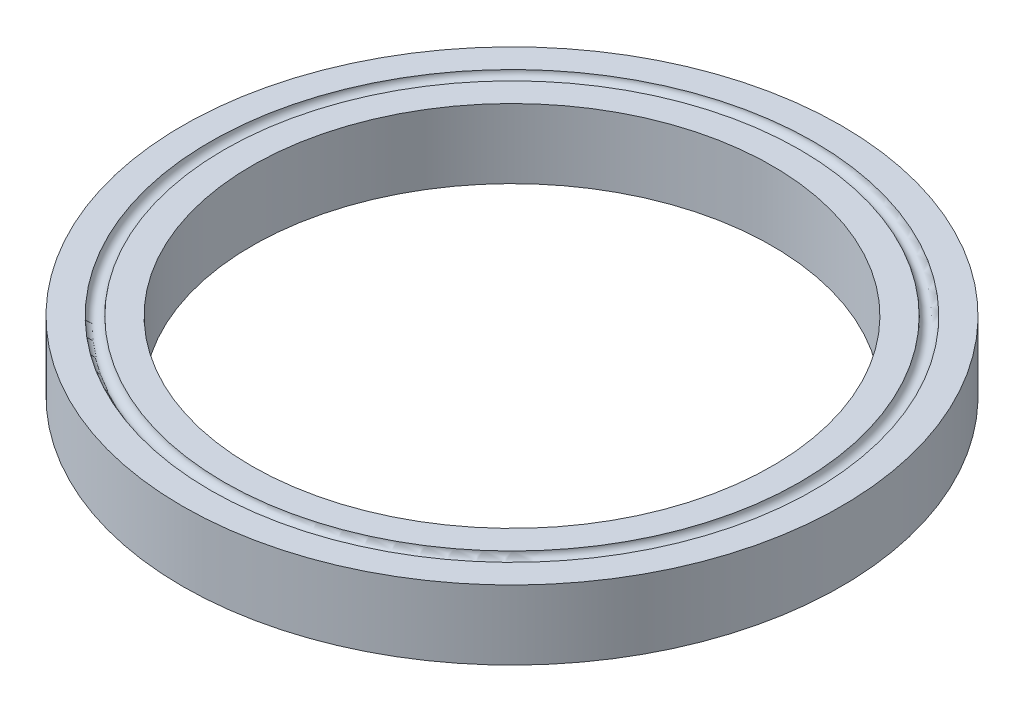
SolidWorks part; units mm, degrees
material "普通碳钢"
ref_plane "前视" through (0, 0, 0) normal (0, 0, 1) x (1, 0, 0)
ref_plane "上视" through (0, 0, 0) normal (0, 1, 0) x (1, 0, 0)
ref_plane "右视" through (0, 0, 0) normal (1, 0, 0) x (0, 0, -1)
sketch "草图1" plane through (0, 0, 0) normal (0, 0, 1) x (1, 0, 0)
  line L0 (0, 0) -> (0, -119.8891) construction
  line L1 (37.5, 0) -> (41.5, 0)
  line L2 (41.5, 0) -> (41.5, 0.7364) construction
  line L5 (43.5, 0) -> (47.5, 0)
  line L6 (47.5, 0) -> (47.5, -10)
  line L7 (47.5, -10) -> (43.5, -10)
  line L8 (37.5, -10) -> (37.5, 0)
  line L10 (37.5, -5) -> (47.5, -5) construction
  line L14 (41.5, -10) -> (37.5, -10)
  arc A0 (41.5, 0) -> (43.5, 0) centre (42.5, 0) ccw
  arc A1 (41.5, -10) -> (43.5, -10) centre (42.5, -10) cw
  dimension "D1" = 75
  dimension "D2" = 95
  dimension "D3" = 10
  dimension "D4" = 83
  dimension "D5" = 2
revolve "旋转1" add sketch "草图1" angle 360 about L0
